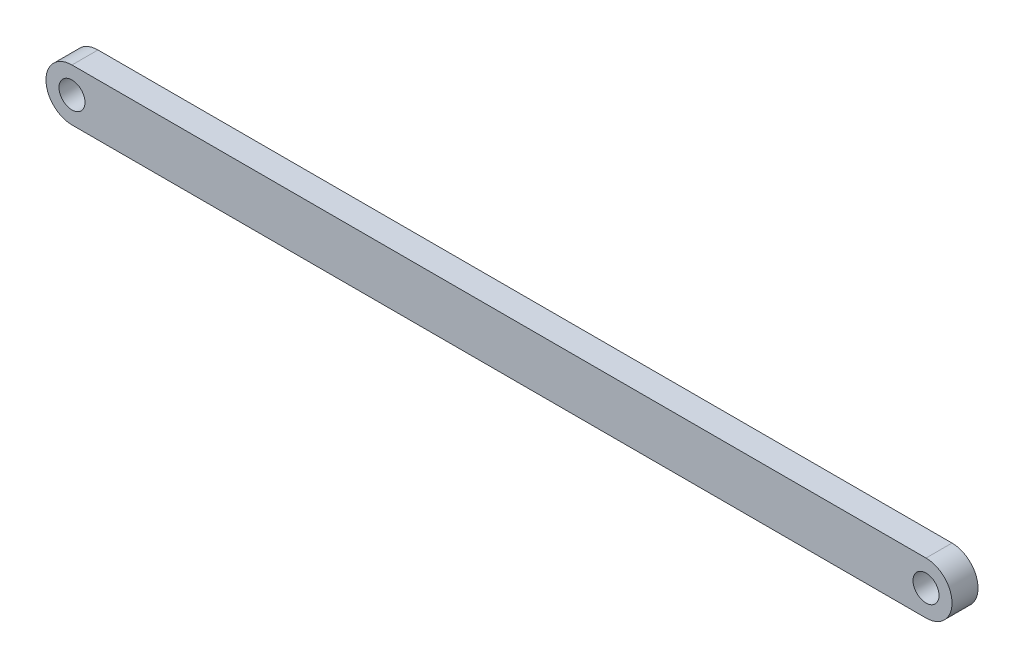
SolidWorks part; units mm, degrees
ref_plane "Plano frontal" through (0, 0, 0) normal (0, 0, 1) x (1, 0, 0)
ref_plane "Plano superior" through (0, 0, 0) normal (0, 1, 0) x (1, 0, 0)
ref_plane "Plano direito" through (0, 0, 0) normal (1, 0, 0) x (0, 0, -1)
sketch "Esboço2" plane through (0, 0, 0) normal (0, 0, 1) x (1, 0, 0)
  line L0 (0, 0) -> (0, 7.0615) construction
  line L1 (-82.16, 7.0615) -> (82.16, 7.0615)
  line L2 (-82.16, 2.0615) -> (82.16, 2.0615) construction
  line L3 (-82.16, -2.9385) -> (82.16, -2.9385)
  arc A0 (-82.16, 7.0615) -> (-82.16, -2.9385) centre (-82.16, 2.0615) ccw
  arc A1 (82.16, 7.0615) -> (82.16, -2.9385) centre (82.16, 2.0615) cw
  circle A2 centre (-82.16, 2.0615) radius 2.5
  circle A3 centre (82.16, 2.0615) radius 2.5
  point P6 (0, 7.0615)
  dimension "D2" = 10
  dimension "D1" = 164.32
extrude "Ressalto-extrusão1" add sketch "Esboço2" along normal blind 5
